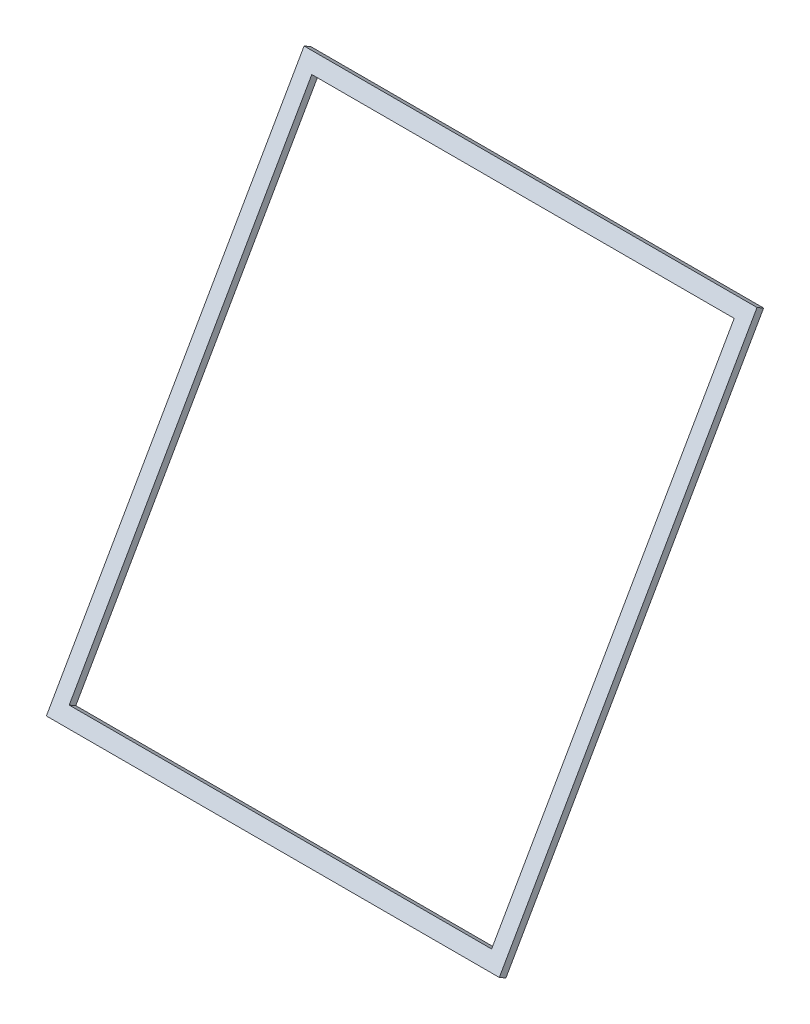
SolidWorks part; units mm, degrees
ref_plane "Alzado" through (0, 0, 0) normal (0, 0, 1) x (1, 0, 0)
ref_plane "Planta" through (0, 0, 0) normal (0, 1, 0) x (1, 0, 0)
ref_plane "Vista lateral" through (0, 0, 0) normal (1, 0, 0) x (0, 0, -1)
ref_plane "Plano1" through (0, 37.2676, 65.2657) normal (0, -0.4959, -0.8684) x (-1, 0, 0)
sketch "Croquis2" plane through (0, 37.2676, 65.2657) normal (0, -0.4959, -0.8684) x (-1, 0, 0)
  line L0 (7.7541, 161.8691) -> (7.7541, -163.3633) construction
  line L1 (-152.2459, 161.8691) -> (167.7541, 161.8691) construction
  line L2 (-130.6395, 139.4235) -> (146.1477, 139.4235)
  line L3 (-140.6395, 149.4235) -> (156.1477, 149.4235)
  line L4 (-140.6395, 149.4235) -> (-140.6395, -191.1467)
  line L5 (-140.6395, -191.1467) -> (156.1477, -191.1467)
  line L6 (156.1477, 149.4235) -> (156.1477, -191.1467)
  line L7 (-140.6395, 149.4235) -> (156.1477, -191.1467) construction
  line L8 (-140.6395, -191.1467) -> (156.1477, 149.4235) construction
  line L9 (146.1477, 139.4235) -> (146.1477, -181.1467)
  line L10 (-130.6395, -181.1467) -> (146.1477, -181.1467)
  line L11 (-130.6395, 139.4235) -> (-130.6395, -181.1467)
  point P4 (7.7541, -20.8616)
  dimension "D1" = 10
extrude "Saliente-Extruir1" add sketch "Croquis2" against normal blind 5
